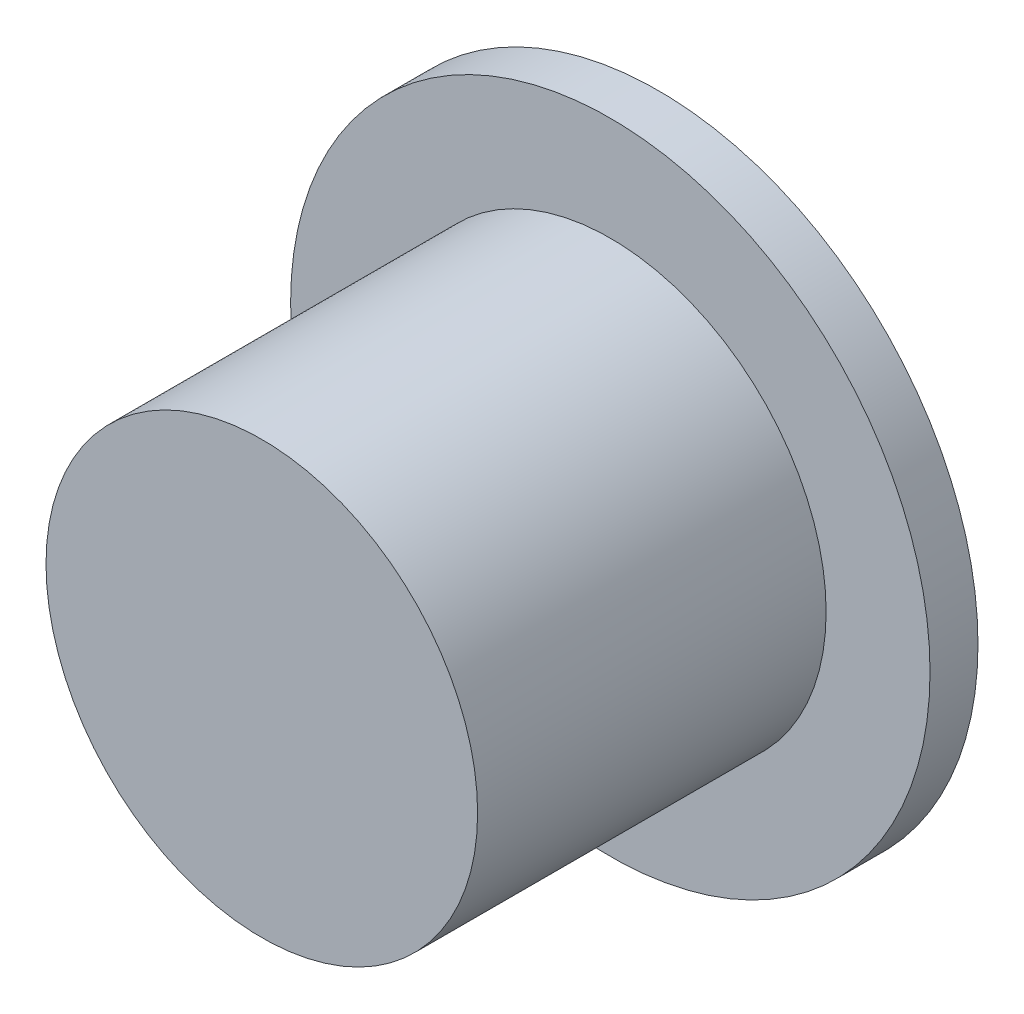
SolidWorks part; units mm, degrees
ref_plane "前基準面" through (0, 0, 0) normal (0, 0, 1) x (1, 0, 0)
ref_plane "上基準面" through (0, 0, 0) normal (0, 1, 0) x (1, 0, 0)
ref_plane "右基準面" through (0, 0, 0) normal (1, 0, 0) x (0, 0, -1)
sketch "草圖1" plane through (0, 0, 0) normal (0, 0, 1) x (1, 0, 0)
  circle A0 centre (-55.9808, -89.6591) radius 10
  dimension "D1" = 20
extrude "填料-伸長1" add sketch "草圖1" along normal blind 1.5
sketch "草圖2" plane through (0, 0, 1.5) normal (0, 0, 1) x (1, 0, 0)
  circle A0 centre (-55.9808, -89.6591) radius 6.75
  circle A1 centre (-55.9808, -89.6591) radius 10 construction
  point P5 (-76.5582, -99.5736)
  dimension "D1" = 13.5
extrude "填料-伸長2" add sketch "草圖2" along normal blind 10.9
sketch "草圖3" plane through (0, 0, 0) normal (0, 0, -1) x (-1, 0, 0)
  circle A0 centre (55.9808, -89.6591) radius 4
  circle A1 centre (55.9808, -89.6591) radius 6.75 construction
  point P5 (92.7727, -90.3059)
  dimension "D1" = 8
extrude "除料-伸長1" cut sketch "草圖3" against normal blind 10
